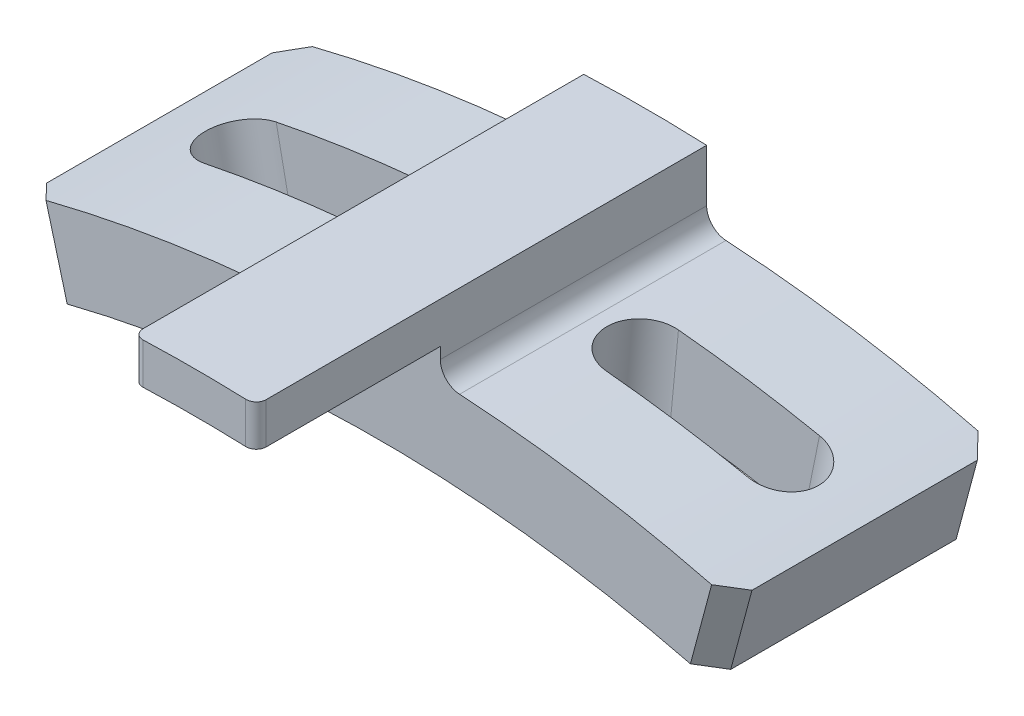
SolidWorks part; units mm, degrees
material "PETG"
ref_plane "Спереди" through (0, 0, 0) normal (0, 0, 1) x (1, 0, 0)
ref_plane "Сверху" through (0, 0, 0) normal (0, 1, 0) x (1, 0, 0)
ref_plane "Справа" through (0, 0, 0) normal (1, 0, 0) x (0, 0, -1)
sketch "Эскиз1" plane through (0, 0, 0) normal (0, 0, 1) x (1, 0, 0)
  line L0 (16.1762, 60.3704) -> (17.2115, 64.2341)
  line L1 (-16.1762, 60.3704) -> (-17.2115, 64.2341)
  line L2 (0, 0) -> (0, 84.5239) construction
  line L3 (-3, 69.9357) -> (-3, 66.4323)
  line L4 (3, 69.9357) -> (3, 66.4323)
  arc A0 (16.1762, 60.3704) -> (-16.1762, 60.3704) centre (0, 0) ccw
  arc A1 (3, 69.9357) -> (-3, 69.9357) centre (0, 0) ccw
  arc A2 (17.2115, 64.2341) -> (3, 66.4323) centre (0, 0) ccw
  circle A3 centre (0, 0) radius 70 construction
  circle A4 centre (0, 0) radius 62.5 construction
  arc A5 (-3, 66.4323) -> (-17.2115, 64.2341) centre (0, 0) ccw
  arc A7 (17.2115, 64.2341) -> (-17.2115, 64.2341) centre (0, 0) ccw construction
  point P6 (59.769, 18.2732)
  point P7 (70, 0)
  dimension "D1" = 125
  dimension "D4" = 4
  dimension "D3" = 15
  dimension "D5" = 6
  dimension "D2" = 7.5
extrude "Бобышка-Вытянуть1" add sketch "Эскиз1" along normal mid plane 13
sketch "Эскиз2" plane through (0, 0, 6.5) normal (0, 0, 1) x (1, 0, 0)
  line L0 (3, 66.4323) -> (3, 69.9357) construction
  line L1 (-3, 69.9357) -> (-3, 66.4323) construction
  line L2 (3, 67.9338) -> (3, 69.9357)
  line L3 (-3, 69.9357) -> (-3, 67.9338)
  arc A0 (3, 69.9357) -> (-3, 69.9357) centre (0, 0) ccw construction
  arc A1 (3, 69.9357) -> (-3, 69.9357) centre (0, 0) ccw
  arc A2 (2.9143, 67.9375) -> (-2.9143, 67.9375) centre (0, 0) ccw construction
  arc A6 (3, 67.9338) -> (-3, 67.9338) centre (0, 0) ccw
  dimension "D1" = 2
extrude "Бобышка-Вытянуть2" add sketch "Эскиз2" along normal blind 9
sketch "Эскиз4" plane through (0, 0, 0) normal (0, 0, 1) x (1, 0, 0)
  line L0 (0, 0) -> (13.258, 65.165) construction
  line L1 (15.1726, 65.7981) -> (13.7383, 58.7483)
  line L4 (13.7383, 58.7483) -> (12.0235, 59.0972)
  line L5 (15.1726, 65.7981) -> (13.4578, 66.147)
  line L6 (12.0235, 59.0972) -> (13.4578, 66.147)
  line L7 (0, 0) -> (0, 62.5) construction
  arc A0 (17.2115, 64.2341) -> (3, 66.4323) centre (0, 0) ccw construction
  arc A1 (16.1762, 60.3704) -> (-16.1762, 60.3704) centre (0, 0) ccw construction
  dimension "D1" = 3.5
  dimension "D2" = 11.5
revolve "Вырез-Повернуть1" cut sketch "Эскиз4" angle 360 about L0
pattern_circular "Круговой массив1" count 2 every 6 about axis through (0, 0, 6.5) along (0, 0, -1) of "Вырез-Повернуть1"
sketch "Эскиз6" plane through (0, 0, 0) normal (0, 0, 1) x (1, 0, 0)
  line L0 (5.9904, 62.2123) -> (6.3737, 66.1938)
  line L1 (12.4605, 61.2453) -> (13.258, 65.165)
  arc A0 (16.1762, 60.3704) -> (-16.1762, 60.3704) centre (0, 0) ccw construction
  arc A1 (17.2115, 64.2341) -> (3, 66.4323) centre (0, 0) ccw construction
  arc A2 (12.4605, 61.2453) -> (5.9904, 62.2123) centre (0, 0) ccw
  arc A3 (13.258, 65.165) -> (6.3737, 66.1938) centre (0, 0) ccw
  arc A8 (7.73, 62.0201) -> (4.2461, 62.3556) centre (0, 0) ccw construction
  arc A10 (8.1135, 66.0032) -> (4.6296, 66.3387) centre (0, 0) ccw construction
  arc A11 (14.1705, 60.8724) -> (10.7407, 61.5702) centre (0, 0) ccw construction
  arc A12 (14.9682, 64.7935) -> (11.5385, 65.4913) centre (0, 0) ccw construction
extrude "Вырез-Вытянуть2" cut sketch "Эскиз6" against normal mid plane 3.5
mirror "Зеркальное отражение1" about plane through (0, 0, 0) normal (1, 0, 0) of "Вырез-Вытянуть2", "Круговой массив1", "Вырез-Повернуть1"
fillet "Скругление1" radius 1 2 edges at (-3, 66.4323, 0) (3, 66.4323, 0)
chamfer "Фаска1" distance 1 angle 45 4 edges at (16.6938, 62.3022, 6.5) (-16.6938, 62.3022, 6.5) (-16.6938, 62.3022, -6.5) (16.6938, 62.3022, -6.5)
fillet "Скругление2" radius 0.5 2 edges at (3, 68.9347, 15.5) (-3, 68.9347, 15.5)
